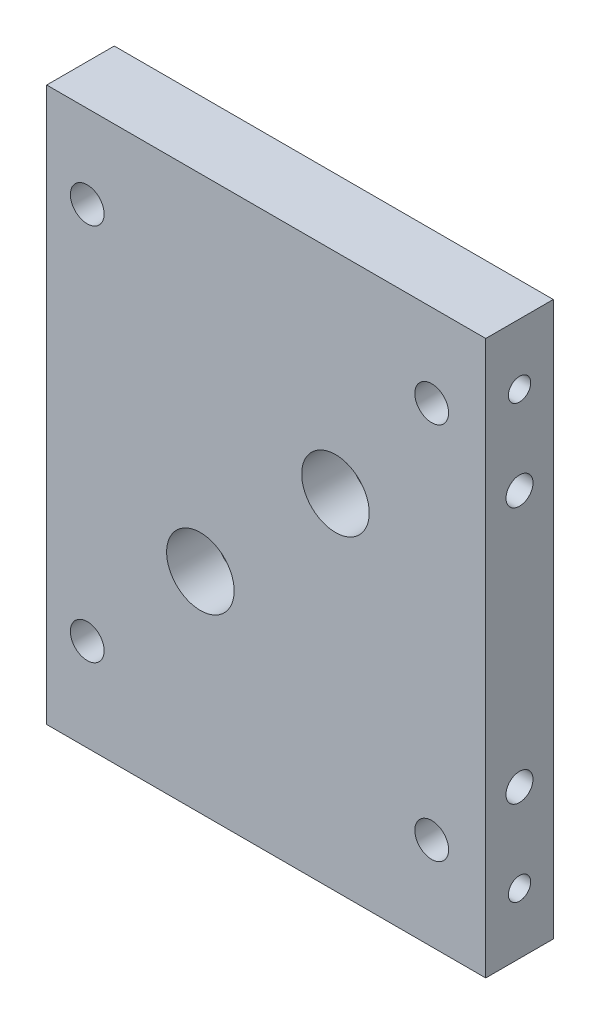
SolidWorks part; units mm, degrees
material "3.1325 (EN-AW 2017A)"
ref_plane "Plan de face" through (0, 0, 0) normal (0, 0, 1) x (1, 0, 0)
ref_plane "Plan de dessus" through (0, 0, 0) normal (0, 1, 0) x (1, 0, 0)
ref_plane "Plan de droite" through (0, 0, 0) normal (1, 0, 0) x (0, 0, -1)
sketch "Esquisse1" plane through (0, 0, 0) normal (0, 0, 1) x (1, 0, 0)
  line L1 (32.5, 41) -> (-32.5, 41)
  line L2 (32.5, 41) -> (32.5, -41)
  line L3 (32.5, -41) -> (-32.5, -41)
  line L4 (-32.5, 41) -> (-32.5, -41)
  line L5 (32.5, 41) -> (-32.5, -41) construction
  line L6 (32.5, -41) -> (-32.5, 41) construction
  point P0 (0, 0)
  dimension "D1" = 65
  dimension "D2" = 82
extrude "Boss.-Extru.1" add sketch "Esquisse1" along normal blind 10
hole_wizard "Trou taraudé M41" [suppressed] positions "Esquisse3" profile "Esquisse2" tap size "M4" standard "ISO"
sketch "Esquisse3" plane through (0, -41, 0) normal (0, -1, 0) x (-1, 0, 0)
  line L0 (32.5, -10) -> (-32.5, -10) construction
  line L4 (32.5, -10) -> (32.5, 0) construction
  point P0 (-2.5, -5)
  point P3 (24.5, -5)
  dimension "D1" = 5
  dimension "D2" = 27
  dimension "D3" = 8
sketch "Esquisse2" plane through (2.5, -41, 5) normal (1, 0, 0) x (0, 0, -1)
  line L0 (0, 0) -> (0, 11.0914)
  line L1 (0, 11.0914) -> (1.65, 10.1)
  line L2 (1.65, 10.1) -> (1.65, 0)
  line L5 (1.65, 0) -> (0, 0)
  line L10 (0, 11.0914) -> (-1.65, 10.1) construction
  line L11 (0, -6.35) -> (0, 107.95) construction
  dimension "Diamètre du trou pour taraudage" = 3.3
  dimension "Profondeur du trou pour taraudage" = 10.1
  dimension "Angle de pointe" = 118
cosmetic thread "Filetage de perçage1" [suppressed] parameters "D1"=8, "D2"=4
cosmetic thread "Filetage de perçage2" [suppressed] parameters "D1"=8, "D2"=4
hole_wizard "Chambrage pour vis à tête hexagonale M51" positions "Esquisse18" profile "Esquisse17" counterbore size "M5" standard "ISO" end condition through all
sketch "Esquisse18" plane through (0, 0, 10) normal (0, 0, 1) x (1, 0, 0)
  point P0 (10.25, 10)
  point P3 (-9.75, -10)
sketch "Esquisse17" plane through (10.25, 10, 10) normal (1, 0, 0) x (0, -1, 0)
  line L0 (0, 0) -> (0, 10)
  line L1 (0, 10) -> (2.75, 10)
  line L3 (2.75, 10) -> (2.75, 7)
  line L4 (2.75, 7) -> (5, 7)
  line L5 (5, 7) -> (5, 0)
  line L7 (5, 0) -> (0, 0)
  line L11 (0, -6.35) -> (0, 107.95) construction
  dimension "Diamètre du perçage jusqu'au prochain" = 5.5
  dimension "Profondeur du perçage jusqu'au prochain" = 10
  dimension "Diamètre du chambrage" = 10
  dimension "Profondeur du chambrage" = 7
hole_wizard "Trou taraudé M42" positions "Esquisse20" profile "Esquisse19" tap size "M4" standard "ISO"
sketch "Esquisse20" plane through (32.5, 0, 0) normal (1, 0, 0) x (0, 0, -1)
  point P0 (-5, -32)
  point P3 (-5, 32)
sketch "Esquisse19" plane through (32.5, -32, 5) normal (0, 1, 0) x (0, 0, -1)
  line L0 (0, 0) -> (0, 12.4914)
  line L1 (0, 12.4914) -> (1.65, 11.5)
  line L2 (1.65, 11.5) -> (1.65, 0)
  line L5 (1.65, 0) -> (0, 0)
  line L10 (0, 12.4914) -> (-1.65, 11.5) construction
  line L11 (0, -6.35) -> (0, 107.95) construction
  dimension "Diamètre du trou pour taraudage" = 3.3
  dimension "Profondeur du trou pour taraudage" = 11.5
  dimension "Angle de pointe" = 118
cosmetic thread "Filetage de perçage3"
cosmetic thread "Filetage de perçage4"
hole_wizard "Trous de centrage Ø4.0mmTransitional 1" positions "Esquisse22" profile "Esquisse21" hole size "Ø4.0" standard "ISO"
sketch "Esquisse22" plane through (32.5, 0, 0) normal (1, 0, 0) x (0, 0, -1)
  point P0 (-5, -19)
  point P3 (-5, 19)
sketch "Esquisse21" plane through (32.5, -19, 5) normal (0, 1, 0) x (0, 0, -1)
  line L0 (0, 0) -> (0, 9.1547)
  line L1 (0, 9.1547) -> (2, 8)
  line L2 (2, 8) -> (2, 0)
  line L5 (2, 0) -> (0, 0)
  line L10 (0, 9.1547) -> (-2, 8) construction
  line L11 (0, -6.35) -> (0, 107.95) construction
  dimension "Diamètre du perçage" = 4
  dimension "Profondeur du perçage" = 8
  dimension "Angle de pointe" = 120
hole_wizard "Trou taraudé M61" positions "Esquisse24" profile "Esquisse23" tap size "M6" standard "ISO" end condition through all
sketch "Esquisse24" plane through (0, 0, 0) normal (0, 0, -1) x (-1, 0, 0)
  point P0 (26.5, 28.7)
  point P2 (-24.5, 28.7)
  point P4 (-24.5, -27.3)
  point P6 (26.5, -27.3)
cosmetic thread "Filetage de perçage5"
cosmetic thread "Filetage de perçage6"
cosmetic thread "Filetage de perçage7"
cosmetic thread "Filetage de perçage8"
sketch "Esquisse23" plane through (-26.5, 28.7, 0) normal (1, 0, 0) x (0, 1, 0)
  line L0 (0, 0) -> (0, 10)
  line L1 (0, 10) -> (2.5, 10)
  line L2 (2.5, 10) -> (2.5, 0)
  line L5 (2.5, 0) -> (0, 0)
  line L11 (0, -6.35) -> (0, 107.95) construction
  dimension "Diamètre du trou pour taraudage jusqu'au prochain" = 5
  dimension "Profondeur du trou pour taraudage jusqu'au prochain" = 10
